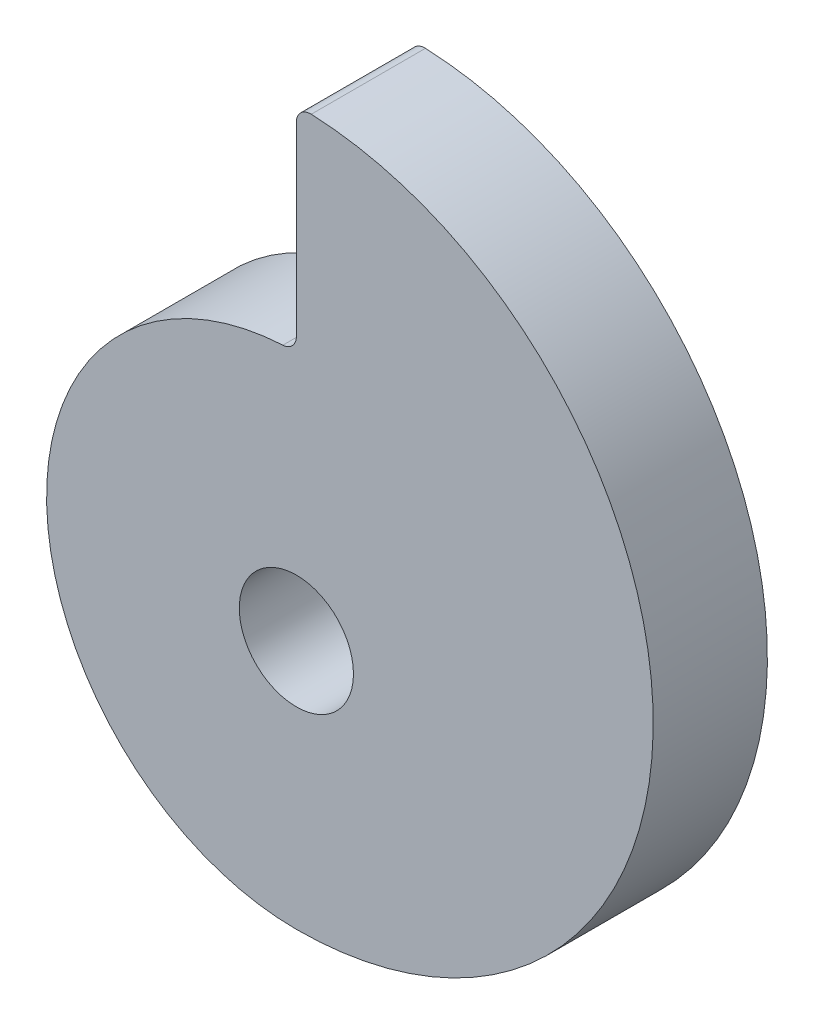
SolidWorks part; units mm, degrees
ref_plane "Front Plane" through (0, 0, 0) normal (0, 0, 1) x (1, 0, 0)
ref_plane "Top Plane" through (0, 0, 0) normal (0, 1, 0) x (1, 0, 0)
ref_plane "Right Plane" through (0, 0, 0) normal (1, 0, 0) x (0, 0, -1)
sketch "Sketch1" plane through (0, 0, 0) normal (0, 0, 1) x (1, 0, 0)
  line L0 (0, 10) -> (0, 25)
  arc A0 (0, -25) -> (0, 25) centre (0, 0) ccw
  arc A2 (0, 10) -> (0, -25) centre (0, -7.5) ccw
  circle A3 centre (0, -7.5) radius 4
extrude "Boss-Extrude1" add sketch "Sketch1" along normal blind 8
fillet "Fillet1" radius 1 2 edges at (0, 25, 4) (0, 10, 4)
